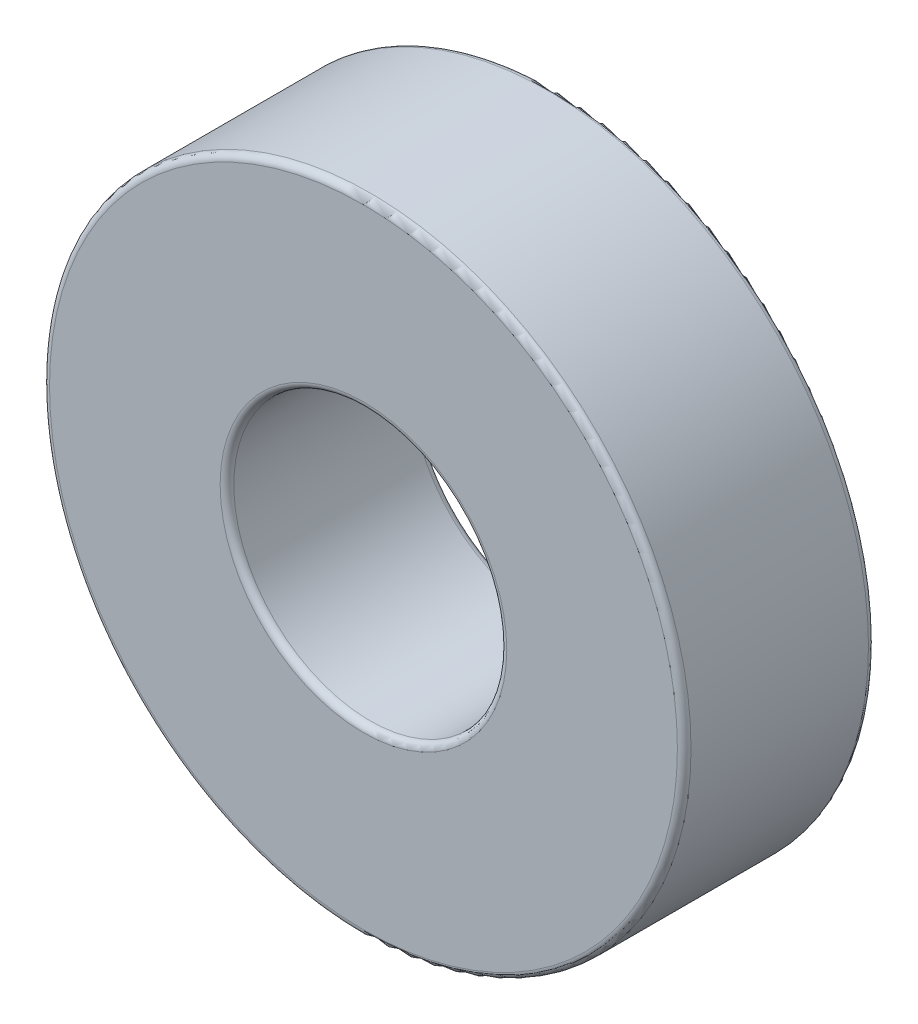
SolidWorks part; units mm, degrees
ref_plane "前视基准面" through (0, 0, 0) normal (0, 0, 1) x (1, 0, 0)
ref_plane "上视基准面" through (0, 0, 0) normal (0, 1, 0) x (1, 0, 0)
ref_plane "右视基准面" through (0, 0, 0) normal (1, 0, 0) x (0, 0, -1)
sketch "草图1" plane through (0, 0, 0) normal (0, 0, 1) x (1, 0, 0)
  circle A0 centre (0, 0) radius 23.5
  circle A1 centre (0, 0) radius 10
extrude "拉伸1" add sketch "草图1" along normal blind 14
fillet "圆角1" radius 0.5 4 edges at (23.5, 0, 0) (23.5, 0, 14) (10, 0, 0) (10, 0, 14)
